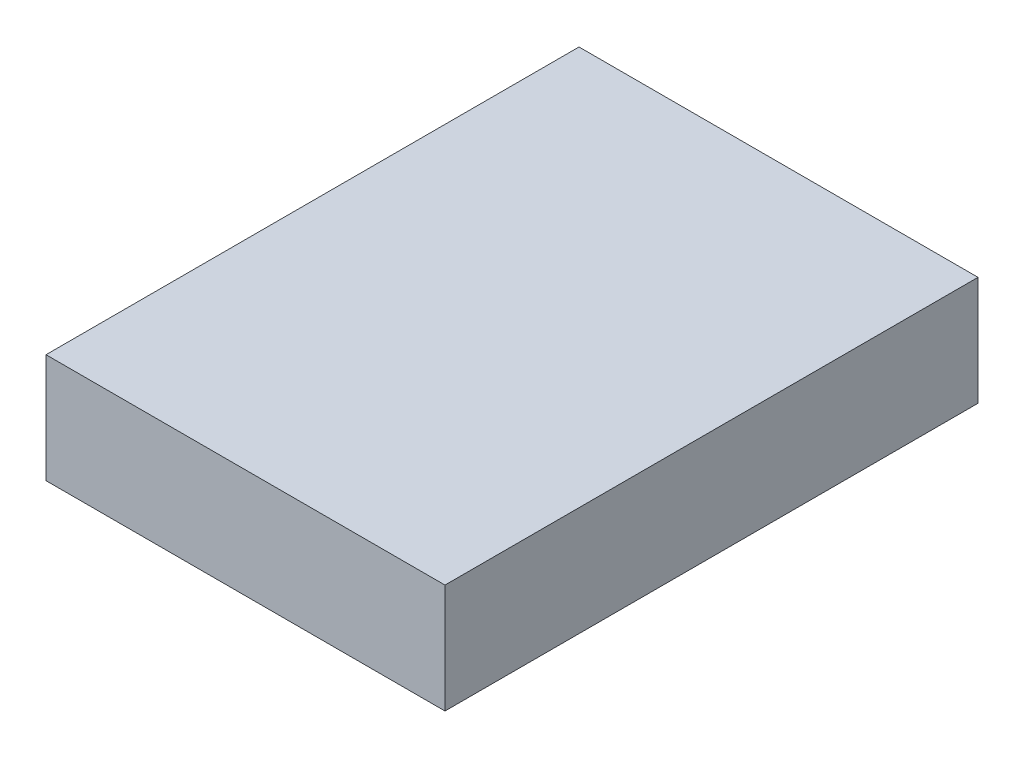
SolidWorks part; units mm, degrees
ref_plane "Alzado" through (0, 0, 0) normal (0, 0, 1) x (1, 0, 0)
ref_plane "Planta" through (0, 0, 0) normal (0, 1, 0) x (1, 0, 0)
ref_plane "Vista lateral" through (0, 0, 0) normal (1, 0, 0) x (0, 0, -1)
sketch "Croquis1" plane through (0, 0, 0) normal (0, 1, 0) x (1, 0, 0)
  line L1 (12.8, -17.1) -> (-12.8, -17.1)
  line L2 (12.8, -17.1) -> (12.8, 17.1)
  line L3 (12.8, 17.1) -> (-12.8, 17.1)
  line L4 (-12.8, -17.1) -> (-12.8, 17.1)
  line L5 (12.8, -17.1) -> (-12.8, 17.1) construction
  line L6 (12.8, 17.1) -> (-12.8, -17.1) construction
  point P0 (0, 0)
  dimension "D1" = 34.2
  dimension "D2" = 25.6
extrude "Saliente-Extruir1" add sketch "Croquis1" along normal blind 7
